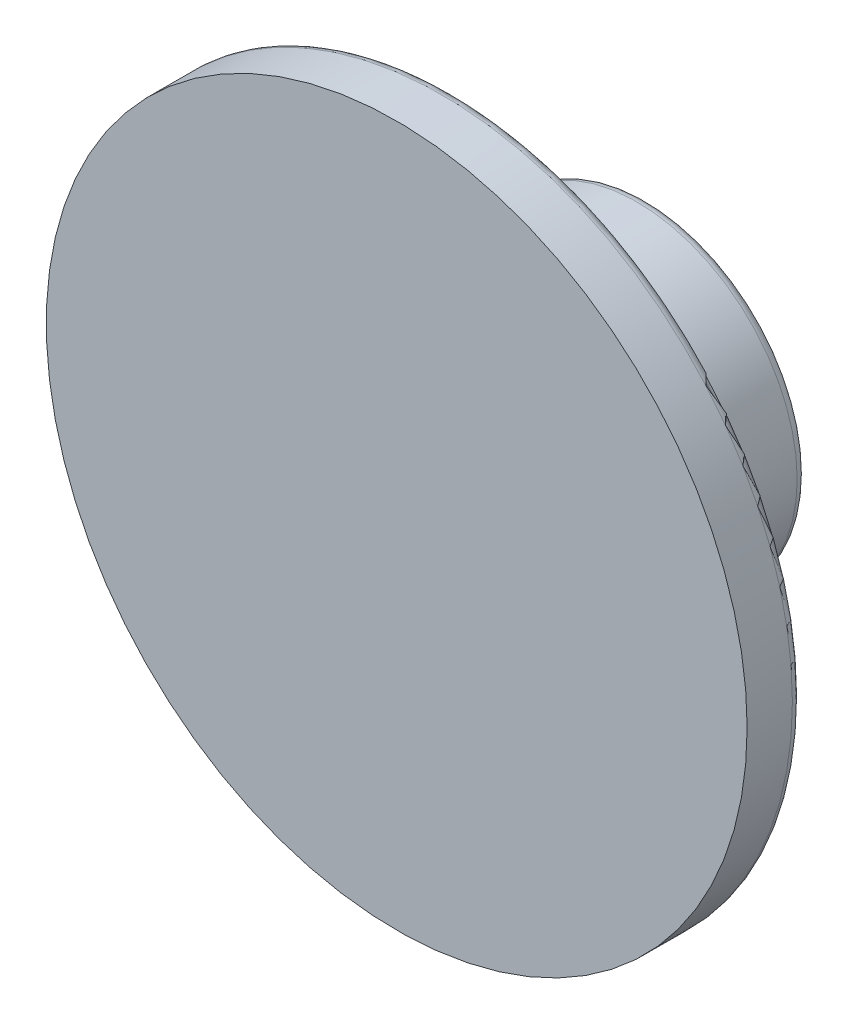
SolidWorks part; units mm, degrees
ref_plane "Front Plane" through (0, 0, 0) normal (0, 0, 1) x (1, 0, 0)
ref_plane "Top Plane" through (0, 0, 0) normal (0, 1, 0) x (1, 0, 0)
ref_plane "Right Plane" through (0, 0, 0) normal (1, 0, 0) x (0, 0, -1)
sketch "Sketch1" plane through (0, 0, 0) normal (0, 1, 0) x (1, 0, 0)
  line L0 (0, 0) -> (-35, 0)
  line L1 (-35, 0) -> (-35, 5.5)
  line L2 (0, 0) -> (0, 15)
  line L3 (0, 15) -> (-6, 15)
  line L4 (-6, 15) -> (-6, 25)
  line L5 (-6, 25) -> (-16, 25)
  line L6 (-16, 25) -> (-16, 15)
  line L7 (-35, 5.5) -> (-8.026, 5.5) construction
  arc A1 (-35, 5.5) -> (-16, 15) centre (-35, 29.25) ccw
  dimension "D1" = 25
  dimension "D2" = 15
  dimension "D3" = 5.5
  dimension "D4" = 35
  dimension "D5" = 6
  dimension "D6" = 16
  dimension "D7" = 10
revolve "Revolve1" add sketch "Sketch1" angle 360 about L2
fillet "Fillet1" radius 1 3 edges at (16, 0, -15) (16, 0, -25) (35, 0, -5.5)
